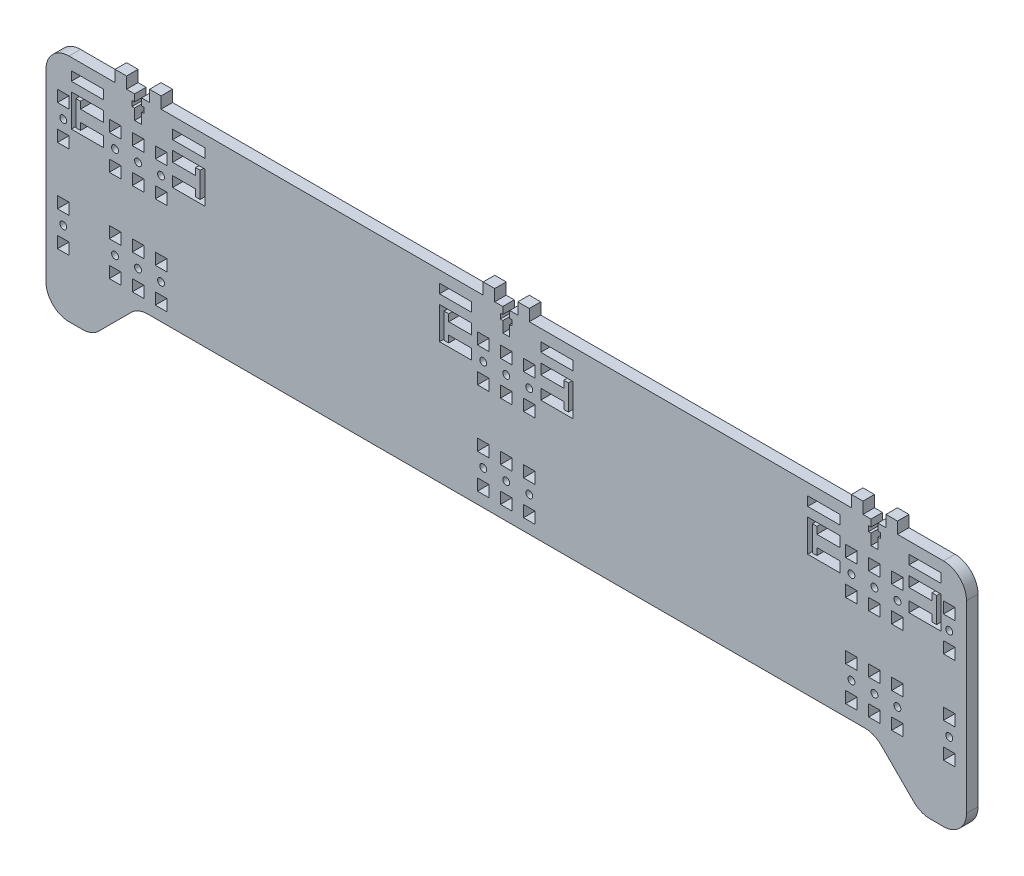
SolidWorks part; units mm, degrees
ref_plane "Front Plane" through (0, 0, 0) normal (0, 0, 1) x (1, 0, 0)
ref_plane "Top Plane" through (0, 0, 0) normal (0, 1, 0) x (1, 0, 0)
ref_plane "Right Plane" through (0, 0, 0) normal (1, 0, 0) x (0, 0, -1)
sketch "Sketch1" plane through (0, 0, 0) normal (0, 0, 1) x (1, 0, 0)
  line L0 (0, 0) -> (194.9917, 0) construction
  line L1 (0, 0) -> (0, -11.2208) construction
  line L2 (1.5, 0) -> (5, 0)
  line L3 (5, 5) -> (10, 5)
  line L4 (10, 5) -> (10, 0)
  line L5 (5, 5) -> (5, 0)
  line L6 (-1.5, 0) -> (-5, 0)
  line L7 (-5, 0) -> (-5, 5)
  line L8 (-5, 5) -> (-10, 5)
  line L9 (-10, 5) -> (-10, 0)
  line L10 (1.5, 0) -> (-1.5, 0) construction
  line L11 (-1.5, 0) -> (-1.5, -3)
  line L12 (-1.5, -5.3) -> (-2.6, -5.3)
  line L13 (2.6, -3) -> (2.6, -5.3)
  line L14 (-2.6, -3) -> (-1.5, -3)
  line L15 (-1.5, -5.3) -> (-1.5, -10)
  line L16 (-1.5, -10) -> (1.5, -10)
  line L17 (1.5, -10) -> (1.5, -5.3)
  line L18 (1.5, -3) -> (2.6, -3)
  line L19 (-2.6, -5.3) -> (-2.6, -3)
  line L20 (2.6, -5.3) -> (1.5, -5.3)
  line L21 (1.5, -3) -> (1.5, 0)
  line L22 (0, -10) -> (0, 0) construction
  line L23 (170, 5) -> (170, 0)
  line L24 (165, 5) -> (170, 5)
  line L25 (165, 5) -> (165, 0)
  line L26 (161.5, 0) -> (165, 0)
  line L27 (161.5, -3) -> (161.5, 0)
  line L28 (161.5, -3) -> (162.6, -3)
  line L29 (162.6, -3) -> (162.6, -5.3)
  line L30 (162.6, -5.3) -> (161.5, -5.3)
  line L31 (161.5, -10) -> (161.5, -5.3)
  line L32 (158.5, -10) -> (161.5, -10)
  line L33 (158.5, -5.3) -> (158.5, -10)
  line L34 (158.5, -5.3) -> (157.4, -5.3)
  line L35 (157.4, -5.3) -> (157.4, -3)
  line L36 (157.4, -3) -> (158.5, -3)
  line L37 (158.5, 0) -> (158.5, -3)
  line L38 (158.5, 0) -> (155, 0)
  line L39 (155, 0) -> (155, 5)
  line L40 (155, 5) -> (150, 5)
  line L41 (150, 5) -> (150, 0)
  line L42 (0, 0) -> (0, -65) construction
  line L43 (-150, 5) -> (-150, 0)
  line L44 (-155, 5) -> (-150, 5)
  line L45 (-155, 0) -> (-155, 5)
  line L46 (-158.5, 0) -> (-155, 0)
  line L47 (-158.5, 0) -> (-158.5, -3)
  line L48 (-157.4, -3) -> (-158.5, -3)
  line L49 (-157.4, -5.3) -> (-157.4, -3)
  line L50 (-158.5, -5.3) -> (-157.4, -5.3)
  line L51 (-158.5, -5.3) -> (-158.5, -10)
  line L52 (-158.5, -10) -> (-161.5, -10)
  line L53 (-161.5, -10) -> (-161.5, -5.3)
  line L54 (-162.6, -5.3) -> (-161.5, -5.3)
  line L55 (-162.6, -3) -> (-162.6, -5.3)
  line L56 (-161.5, -3) -> (-162.6, -3)
  line L57 (-161.5, -3) -> (-161.5, 0)
  line L58 (-161.5, 0) -> (-165, 0)
  line L59 (-165, 5) -> (-165, 0)
  line L60 (-165, 5) -> (-170, 5)
  line L61 (-170, 5) -> (-170, 0)
  line L63 (-10, 0) -> (-150, 0)
  line L64 (-170, 0) -> (-200, 0)
  line L65 (-200, 0) -> (-200, -100)
  line L66 (-200, -100) -> (200, -100) construction
  line L67 (200, -100) -> (200, 0)
  line L68 (200, 0) -> (170, 0)
  line L69 (10, 0) -> (150, 0)
  line L70 (-200, -65) -> (200, -65) construction
  line L71 (-160, -10) -> (-160, -65) construction
  line L72 (160, -10) -> (160, -65) construction
  line L73 (-150, -25) -> (-150, -65) construction
  line L74 (-200, -100) -> (-180, -100)
  line L75 (-180, -100) -> (-160, -80)
  line L76 (-160, -80) -> (160, -80)
  line L77 (160, -80) -> (180, -100)
  line L78 (180, -100) -> (200, -100)
  point P31 (0, -34.8981)
  line B0 (150, -60) -> (150, -70) construction
  line B1 (152.5, -60) -> (152.5, -55)
  line B2 (152.5, -60) -> (147.5, -60)
  line B3 (147.5, -60) -> (147.5, -55)
  line B4 (152.5, -55) -> (147.5, -55)
  line B5 (152.5, -70) -> (152.5, -75)
  line B6 (152.5, -70) -> (147.5, -70)
  line B7 (147.5, -70) -> (147.5, -75)
  line B8 (152.5, -75) -> (147.5, -75)
  line B9 (150, -65) -> (156.9724, -65) construction
  circle B10 centre (150, -65) radius 1.5
  line B11 (10, -60) -> (10, -70) construction
  line B12 (12.5, -60) -> (12.5, -55)
  line B13 (12.5, -60) -> (7.5, -60)
  line B14 (7.5, -60) -> (7.5, -55)
  line B15 (12.5, -55) -> (7.5, -55)
  line B16 (12.5, -70) -> (12.5, -75)
  line B17 (12.5, -70) -> (7.5, -70)
  line B18 (7.5, -70) -> (7.5, -75)
  line B19 (12.5, -75) -> (7.5, -75)
  line B20 (10, -65) -> (16.9724, -65) construction
  circle B21 centre (10, -65) radius 1.5
  line B22 (-150, -60) -> (-150, -70) construction
  line B23 (-147.5, -60) -> (-147.5, -55)
  line B24 (-147.5, -60) -> (-152.5, -60)
  line B25 (-152.5, -60) -> (-152.5, -55)
  line B26 (-147.5, -55) -> (-152.5, -55)
  line B27 (-147.5, -70) -> (-147.5, -75)
  line B28 (-147.5, -70) -> (-152.5, -70)
  line B29 (-152.5, -70) -> (-152.5, -75)
  line B30 (-147.5, -75) -> (-152.5, -75)
  line B31 (-150, -65) -> (-143.0276, -65) construction
  circle B32 centre (-150, -65) radius 1.5
  line B33 (-150, -20) -> (-150, -30) construction
  line B34 (-147.5, -20) -> (-147.5, -15)
  line B35 (-147.5, -20) -> (-152.5, -20)
  line B36 (-152.5, -20) -> (-152.5, -15)
  line B37 (-147.5, -15) -> (-152.5, -15)
  line B38 (-147.5, -30) -> (-147.5, -35)
  line B39 (-147.5, -30) -> (-152.5, -30)
  line B40 (-152.5, -30) -> (-152.5, -35)
  line B41 (-147.5, -35) -> (-152.5, -35)
  line B42 (-150, -25) -> (-143.0276, -25) construction
  circle B43 centre (-150, -25) radius 1.5
  line B44 (10, -20) -> (10, -30) construction
  line B45 (12.5, -20) -> (12.5, -15)
  line B46 (12.5, -20) -> (7.5, -20)
  line B47 (7.5, -20) -> (7.5, -15)
  line B48 (12.5, -15) -> (7.5, -15)
  line B49 (12.5, -30) -> (12.5, -35)
  line B50 (12.5, -30) -> (7.5, -30)
  line B51 (7.5, -30) -> (7.5, -35)
  line B52 (12.5, -35) -> (7.5, -35)
  line B53 (10, -25) -> (16.9724, -25) construction
  circle B54 centre (10, -25) radius 1.5
  line B55 (150, -20) -> (150, -30) construction
  line B56 (152.5, -20) -> (152.5, -15)
  line B57 (152.5, -20) -> (147.5, -20)
  line B58 (147.5, -20) -> (147.5, -15)
  line B59 (152.5, -15) -> (147.5, -15)
  line B60 (152.5, -30) -> (152.5, -35)
  line B61 (152.5, -30) -> (147.5, -30)
  line B62 (147.5, -30) -> (147.5, -35)
  line B63 (152.5, -35) -> (147.5, -35)
  line B64 (150, -25) -> (156.9724, -25) construction
  circle B65 centre (150, -25) radius 1.5
  line B66 (192.5, -20) -> (192.5, -30) construction
  line B67 (195, -20) -> (195, -15)
  line B68 (195, -20) -> (190, -20)
  line B69 (190, -20) -> (190, -15)
  line B70 (195, -15) -> (190, -15)
  line B71 (195, -30) -> (195, -35)
  line B72 (195, -30) -> (190, -30)
  line B73 (190, -30) -> (190, -35)
  line B74 (195, -35) -> (190, -35)
  line B75 (192.5, -25) -> (199.4724, -25) construction
  circle B76 centre (192.5, -25) radius 1.5
  line B77 (192.5, -60) -> (192.5, -70) construction
  line B78 (195, -60) -> (195, -55)
  line B79 (195, -60) -> (190, -60)
  line B80 (190, -60) -> (190, -55)
  line B81 (195, -55) -> (190, -55)
  line B82 (195, -70) -> (195, -75)
  line B83 (195, -70) -> (190, -70)
  line B84 (190, -70) -> (190, -75)
  line B85 (195, -75) -> (190, -75)
  line B86 (192.5, -65) -> (199.4724, -65) construction
  circle B87 centre (192.5, -65) radius 1.5
  line B88 (-192.5, -60) -> (-192.5, -70) construction
  line B89 (-190, -60) -> (-190, -55)
  line B90 (-190, -60) -> (-195, -60)
  line B91 (-195, -60) -> (-195, -55)
  line B92 (-190, -55) -> (-195, -55)
  line B93 (-190, -70) -> (-190, -75)
  line B94 (-190, -70) -> (-195, -70)
  line B95 (-195, -70) -> (-195, -75)
  line B96 (-190, -75) -> (-195, -75)
  line B97 (-192.5, -65) -> (-185.5276, -65) construction
  circle B98 centre (-192.5, -65) radius 1.5
  line B99 (-192.5, -20) -> (-192.5, -30) construction
  line B100 (-190, -20) -> (-190, -15)
  line B101 (-190, -20) -> (-195, -20)
  line B102 (-195, -20) -> (-195, -15)
  line B103 (-190, -15) -> (-195, -15)
  line B104 (-190, -30) -> (-190, -35)
  line B105 (-190, -30) -> (-195, -30)
  line B106 (-195, -30) -> (-195, -35)
  line B107 (-190, -35) -> (-195, -35)
  line B108 (-192.5, -25) -> (-185.5276, -25) construction
  circle B109 centre (-192.5, -25) radius 1.5
  line B110 (172.5, -20) -> (172.5, -15)
  line B111 (172.5, -20) -> (167.5, -20)
  line B112 (167.5, -20) -> (167.5, -15)
  line B113 (172.5, -15) -> (167.5, -15)
  line B114 (172.5, -30) -> (172.5, -35)
  line B115 (172.5, -30) -> (167.5, -30)
  line B116 (167.5, -30) -> (167.5, -35)
  line B117 (172.5, -35) -> (167.5, -35)
  line B118 (170, -25) -> (176.9724, -25) construction
  circle B119 centre (170, -25) radius 1.5
  line B120 (172.5, -60) -> (172.5, -55)
  line B121 (172.5, -60) -> (167.5, -60)
  line B122 (167.5, -60) -> (167.5, -55)
  line B123 (172.5, -55) -> (167.5, -55)
  line B124 (172.5, -70) -> (172.5, -75)
  line B125 (172.5, -70) -> (167.5, -70)
  line B126 (167.5, -70) -> (167.5, -75)
  line B127 (172.5, -75) -> (167.5, -75)
  line B128 (170, -65) -> (176.9724, -65) construction
  circle B129 centre (170, -65) radius 1.5
  line B130 (-12.5, -60) -> (-12.5, -55)
  line B131 (-12.5, -60) -> (-7.5, -60)
  line B132 (-7.5, -60) -> (-7.5, -55)
  line B133 (-12.5, -55) -> (-7.5, -55)
  line B134 (-12.5, -70) -> (-12.5, -75)
  line B135 (-12.5, -70) -> (-7.5, -70)
  line B136 (-7.5, -70) -> (-7.5, -75)
  line B137 (-12.5, -75) -> (-7.5, -75)
  circle B138 centre (-10, -65) radius 1.5
  line B139 (-12.5, -20) -> (-12.5, -15)
  line B140 (-12.5, -20) -> (-7.5, -20)
  line B141 (-7.5, -20) -> (-7.5, -15)
  line B142 (-12.5, -15) -> (-7.5, -15)
  line B143 (-12.5, -30) -> (-12.5, -35)
  line B144 (-12.5, -30) -> (-7.5, -30)
  line B145 (-7.5, -30) -> (-7.5, -35)
  line B146 (-12.5, -35) -> (-7.5, -35)
  line B147 (-10, -25) -> (-16.9724, -25) construction
  circle B148 centre (-10, -25) radius 1.5
  line B149 (-172.5, -60) -> (-172.5, -55)
  line B150 (-172.5, -60) -> (-167.5, -60)
  line B151 (-167.5, -60) -> (-167.5, -55)
  line B152 (-172.5, -55) -> (-167.5, -55)
  line B153 (-172.5, -70) -> (-172.5, -75)
  line B154 (-172.5, -70) -> (-167.5, -70)
  line B155 (-167.5, -70) -> (-167.5, -75)
  line B156 (-172.5, -75) -> (-167.5, -75)
  circle B157 centre (-170, -65) radius 1.5
  line B158 (-172.5, -20) -> (-172.5, -15)
  line B159 (-172.5, -20) -> (-167.5, -20)
  line B160 (-167.5, -20) -> (-167.5, -15)
  line B161 (-172.5, -15) -> (-167.5, -15)
  line B162 (-172.5, -30) -> (-172.5, -35)
  line B163 (-172.5, -30) -> (-167.5, -30)
  line B164 (-167.5, -30) -> (-167.5, -35)
  line B165 (-172.5, -35) -> (-167.5, -35)
  circle B166 centre (-170, -25) radius 1.5
  line B167 (-145, -17.5) -> (-135, -17.5)
  line B168 (-145, -5) -> (-131, -5)
  line B169 (-145, -5) -> (-145, -9)
  line B170 (-145, -9) -> (-131, -9)
  line B171 (-131, -5) -> (-131, -9)
  line B172 (-135, -17.5) -> (-135, -14.5)
  line B173 (-135, -14.5) -> (-133, -14.5)
  line B174 (-133, -14.5) -> (-133, -25.5)
  line B175 (-133, -25.5) -> (-135, -25.5)
  line B176 (-135, -25.5) -> (-135, -22.5)
  line B177 (-135, -22.5) -> (-145, -22.5)
  line B178 (-145, -22.5) -> (-145, -27)
  line B179 (-145, -27) -> (-131, -27)
  line B180 (-131, -27) -> (-131, -13)
  line B181 (-131, -13) -> (-145, -13)
  line B182 (-145, -13) -> (-145, -17.5)
  line B183 (15, -17.5) -> (25, -17.5)
  line B184 (15, -5) -> (29, -5)
  line B185 (15, -5) -> (15, -9)
  line B186 (15, -9) -> (29, -9)
  line B187 (29, -5) -> (29, -9)
  line B188 (25, -17.5) -> (25, -14.5)
  line B189 (25, -14.5) -> (27, -14.5)
  line B190 (27, -14.5) -> (27, -25.5)
  line B191 (27, -25.5) -> (25, -25.5)
  line B192 (25, -25.5) -> (25, -22.5)
  line B193 (25, -22.5) -> (15, -22.5)
  line B194 (15, -22.5) -> (15, -27)
  line B195 (15, -27) -> (29, -27)
  line B196 (29, -27) -> (29, -13)
  line B197 (29, -13) -> (15, -13)
  line B198 (15, -13) -> (15, -17.5)
  line B199 (175, -17.5) -> (185, -17.5)
  line B200 (175, -5) -> (189, -5)
  line B201 (175, -5) -> (175, -9)
  line B202 (175, -9) -> (189, -9)
  line B203 (189, -5) -> (189, -9)
  line B204 (185, -17.5) -> (185, -14.5)
  line B205 (185, -14.5) -> (187, -14.5)
  line B206 (187, -14.5) -> (187, -25.5)
  line B207 (187, -25.5) -> (185, -25.5)
  line B208 (185, -25.5) -> (185, -22.5)
  line B209 (185, -22.5) -> (175, -22.5)
  line B210 (175, -22.5) -> (175, -27)
  line B211 (175, -27) -> (189, -27)
  line B212 (189, -27) -> (189, -13)
  line B213 (189, -13) -> (175, -13)
  line B214 (175, -13) -> (175, -17.5)
  line B215 (145, -17.5) -> (135, -17.5)
  line B216 (145, -5) -> (131, -5)
  line B217 (145, -5) -> (145, -9)
  line B218 (145, -9) -> (131, -9)
  line B219 (131, -5) -> (131, -9)
  line B220 (135, -17.5) -> (135, -14.5)
  line B221 (135, -14.5) -> (133, -14.5)
  line B222 (133, -14.5) -> (133, -25.5)
  line B223 (133, -25.5) -> (135, -25.5)
  line B224 (135, -25.5) -> (135, -22.5)
  line B225 (135, -22.5) -> (145, -22.5)
  line B226 (145, -22.5) -> (145, -27)
  line B227 (145, -27) -> (131, -27)
  line B228 (131, -27) -> (131, -13)
  line B229 (131, -13) -> (145, -13)
  line B230 (145, -13) -> (145, -17.5)
  line B231 (-15, -17.5) -> (-25, -17.5)
  line B232 (-15, -5) -> (-29, -5)
  line B233 (-15, -5) -> (-15, -9)
  line B234 (-15, -9) -> (-29, -9)
  line B235 (-29, -5) -> (-29, -9)
  line B236 (-25, -17.5) -> (-25, -14.5)
  line B237 (-25, -14.5) -> (-27, -14.5)
  line B238 (-27, -14.5) -> (-27, -25.5)
  line B239 (-27, -25.5) -> (-25, -25.5)
  line B240 (-25, -25.5) -> (-25, -22.5)
  line B241 (-25, -22.5) -> (-15, -22.5)
  line B242 (-15, -22.5) -> (-15, -27)
  line B243 (-15, -27) -> (-29, -27)
  line B244 (-29, -27) -> (-29, -13)
  line B245 (-29, -13) -> (-15, -13)
  line B246 (-15, -13) -> (-15, -17.5)
  line B247 (-175, -17.5) -> (-185, -17.5)
  line B248 (-175, -5) -> (-189, -5)
  line B249 (-175, -5) -> (-175, -9)
  line B250 (-175, -9) -> (-189, -9)
  line B251 (-189, -5) -> (-189, -9)
  line B252 (-185, -17.5) -> (-185, -14.5)
  line B253 (-185, -14.5) -> (-187, -14.5)
  line B254 (-187, -14.5) -> (-187, -25.5)
  line B255 (-187, -25.5) -> (-185, -25.5)
  line B256 (-185, -25.5) -> (-185, -22.5)
  line B257 (-185, -22.5) -> (-175, -22.5)
  line B258 (-175, -22.5) -> (-175, -27)
  line B259 (-175, -27) -> (-189, -27)
  line B260 (-189, -27) -> (-189, -13)
  line B261 (-189, -13) -> (-175, -13)
  line B262 (-175, -13) -> (-175, -17.5)
  line B263 (2.5, -60) -> (2.5, -55)
  line B264 (2.5, -60) -> (-2.5, -60)
  line B265 (-2.5, -60) -> (-2.5, -55)
  line B266 (2.5, -55) -> (-2.5, -55)
  line B267 (2.5, -70) -> (2.5, -75)
  line B268 (2.5, -70) -> (-2.5, -70)
  line B269 (-2.5, -70) -> (-2.5, -75)
  line B270 (2.5, -75) -> (-2.5, -75)
  circle B271 centre (0, -65) radius 1.5
  line B272 (2.5, -20) -> (2.5, -15)
  line B273 (2.5, -20) -> (-2.5, -20)
  line B274 (-2.5, -20) -> (-2.5, -15)
  line B275 (2.5, -15) -> (-2.5, -15)
  line B276 (2.5, -30) -> (2.5, -35)
  line B277 (2.5, -30) -> (-2.5, -30)
  line B278 (-2.5, -30) -> (-2.5, -35)
  line B279 (2.5, -35) -> (-2.5, -35)
  line B280 (0, -25) -> (6.9724, -25) construction
  circle B281 centre (0, -25) radius 1.5
  line B282 (-157.5, -20) -> (-157.5, -15)
  line B283 (-157.5, -20) -> (-162.5, -20)
  line B284 (-162.5, -20) -> (-162.5, -15)
  line B285 (-157.5, -15) -> (-162.5, -15)
  line B286 (-157.5, -30) -> (-157.5, -35)
  line B287 (-157.5, -30) -> (-162.5, -30)
  line B288 (-162.5, -30) -> (-162.5, -35)
  line B289 (-157.5, -35) -> (-162.5, -35)
  line B290 (-160, -25) -> (-153.0276, -25) construction
  circle B291 centre (-160, -25) radius 1.5
  line B292 (-157.5, -60) -> (-157.5, -55)
  line B293 (-157.5, -60) -> (-162.5, -60)
  line B294 (-162.5, -60) -> (-162.5, -55)
  line B295 (-157.5, -55) -> (-162.5, -55)
  line B296 (-157.5, -70) -> (-157.5, -75)
  line B297 (-157.5, -70) -> (-162.5, -70)
  line B298 (-162.5, -70) -> (-162.5, -75)
  line B299 (-157.5, -75) -> (-162.5, -75)
  circle B300 centre (-160, -65) radius 1.5
  line B301 (162.5, -20) -> (162.5, -15)
  line B302 (162.5, -20) -> (157.5, -20)
  line B303 (157.5, -20) -> (157.5, -15)
  line B304 (162.5, -15) -> (157.5, -15)
  line B305 (162.5, -30) -> (162.5, -35)
  line B306 (162.5, -30) -> (157.5, -30)
  line B307 (157.5, -30) -> (157.5, -35)
  line B308 (162.5, -35) -> (157.5, -35)
  line B309 (160, -25) -> (166.9724, -25) construction
  circle B310 centre (160, -25) radius 1.5
  line B311 (162.5, -60) -> (162.5, -55)
  line B312 (162.5, -60) -> (157.5, -60)
  line B313 (157.5, -60) -> (157.5, -55)
  line B314 (162.5, -55) -> (157.5, -55)
  line B315 (162.5, -70) -> (162.5, -75)
  line B316 (162.5, -70) -> (157.5, -70)
  line B317 (157.5, -70) -> (157.5, -75)
  line B318 (162.5, -75) -> (157.5, -75)
  line B319 (160, -65) -> (166.9724, -65) construction
  circle B320 centre (160, -65) radius 1.5
  dimension "D1" = 10
  dimension "D2" = 25
  dimension "D3" = 5
  dimension "D4" = 5.2
  dimension "D5" = 3
  dimension "D6" = 2.3
  dimension "D7" = 3
  dimension "D8" = 10
  dimension "D10" = 40
  dimension "D11" = 30
  dimension "D12" = 100
  dimension "D13" = 160
  dimension "D14" = 10
  dimension "D15" = 5
  dimension "D16" = 10
  dimension "D17" = 10
  dimension "D18" = 5
  dimension "D19" = 20
  dimension "D20" = 80
  dimension "D21" = 20
  dimension "D24" = 15
  dimension "D27" = 15
  dimension "D28" = 15
  dimension "D9" = 2
sketch_block_instance "Trou M3 plots 5mm-1"
sketch_block "Block1" parameters "D2"=3, "D1"=5, "D3"=5, "D4"=10
sketch_block_instance "Block1-1"
sketch_block_instance "Block1-2"
sketch_block_instance "Block1-3"
sketch_block_instance "Block1-4"
sketch_block_instance "Block1-5"
sketch_block_instance "Block1-7"
sketch_block_instance "Block1-8"
sketch_block_instance "Block1-9"
sketch_block_instance "Block1-10"
sketch_block_instance "Block1-16"
sketch_block_instance "Block1-17"
sketch_block_instance "Block1-27"
sketch_block_instance "Block1-28"
sketch_block_instance "Block1-29"
sketch_block_instance "Block1-30"
sketch_block_instance "Bloc1-5"
sketch_block "Bloc1" parameters "D1"=10, "D2"=2, "D3"=2, "D4"=3, "D5"=1.5, "D6"=5, "D7"=4, "D8"=4
sketch_block_instance "Bloc1-6"
sketch_block_instance "Bloc1-7"
sketch_block_instance "Bloc1-8"
sketch_block_instance "Bloc1-9"
sketch_block_instance "Bloc1-10"
sketch_block_instance "Block1-31"
sketch_block_instance "Block1-32"
sketch_block_instance "Block1-35"
sketch_block_instance "Block1-36"
sketch_block_instance "Block1-37"
sketch_block_instance "Block1-38"
extrude "Boss-Extrude1" add sketch "Sketch1" along normal blind 5
fillet "Congé1" radius 10 8 edges at (200, 0, 2.5) (-200, 0, 2.5) (200, -100, 2.5) (180, -100, 2.5) (160, -80, 2.5) (-160, -80, 2.5) (-180, -100, 2.5) (-200, -100, 2.5)
